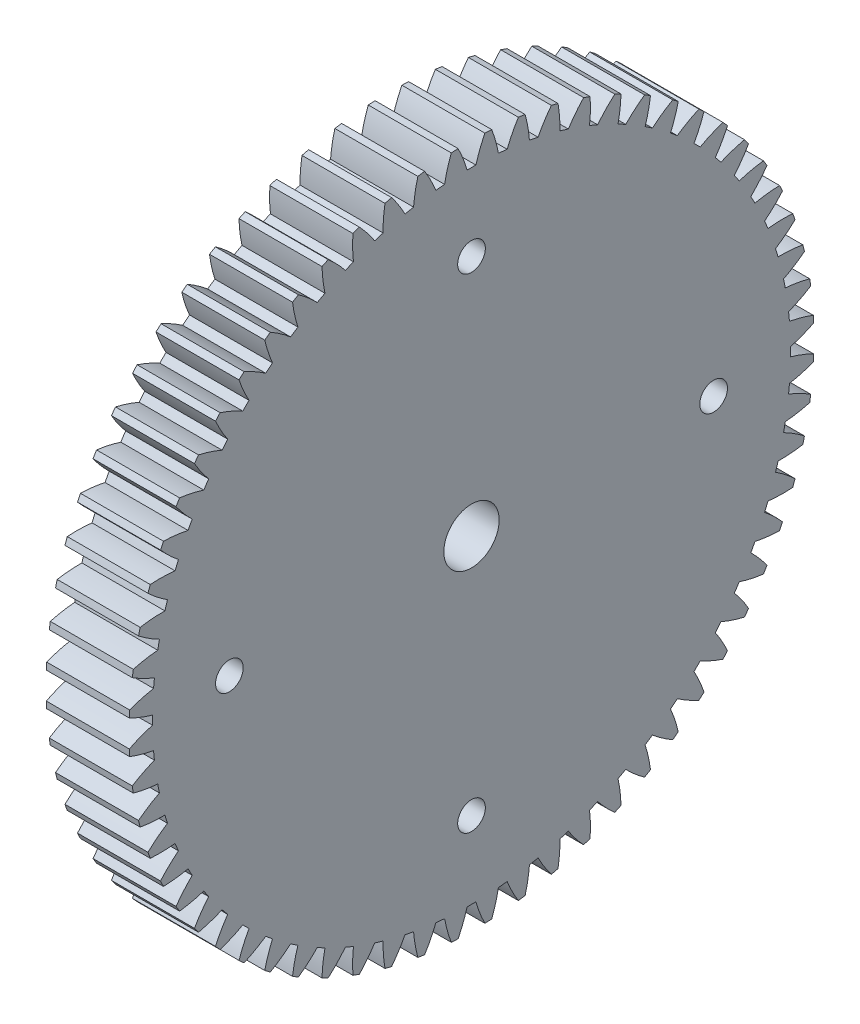
SolidWorks part; units mm, degrees
ref_plane "Plane1" through (0, 0, 0) normal (0, 0, 1) x (1, 0, 0)
ref_plane "Plane2" through (0, 0, 0) normal (0, 1, 0) x (1, 0, 0)
ref_plane "Plane3" through (0, 0, 0) normal (1, 0, 0) x (0, 0, -1)
sketch "HoldingSke" plane through (0, 0, 0) normal (0, 1, 0) x (1, 0, 0)
  line L0 (0, 0) -> (0.2922, -0.5992)
  line L1 (-15, 0) -> (100, 0) construction
  line L2 (0, 0) -> (-2.1039, 2.3779)
  line L3 (0, 0) -> (-11.863, 4.5341)
  line L4 (0, 0) -> (3.7858, 7.762)
  line L5 (0, 0) -> (-46.8476, -17.4728)
  line L6 (0, 0) -> (-9.9476, -6.7116)
  line L7 (-2.1039, 2.3779) -> (8.6586, 51.2059)
  line L8 (-76.2, 54.61) -> (-74.8, 54.61)
  line L9 (-71.009, 38.7566) -> (-53.1078, 45.2721)
  line L10 (-76.2, 71.12) -> (104.1128, 71.12)
  line L11 (0, 0) -> (-12, 0)
  line L12 (-76.2, 101.6) -> (-76.147, 101.6)
  line L13 (24.9733, 27.94) -> (52.9518, 28.4284)
  line L14 (24.9733, 27.94) -> (24.9743, 27.94)
  line L15 (24.9733, 27.94) -> (100.4006, 29.5858)
  line L16 (-63.627, -1.5) -> (-12.827, -1.5)
  circle A0 centre (0, 0) radius 4
  circle A1 centre (0, 0) radius 37.5
  circle A2 centre (0, 0) radius 37.5
  circle A3 centre (0, 0) radius 4
  dimension "MHD" = 75
  dimension "Hub_dia" = 75
  dimension "Bore" = 8
  dimension "MBD" = 8
  dimension "Num_teeth" = 64
  dimension "Pitch" = 0.6667
  dimension "Overall_len" = 50
  dimension "Show_teeth" = 64
  dimension "Thickness" = 12
  dimension "OAL" = 50.0001
  dimension "T_dim" = 1.4
  dimension "Ap" = 20
  dimension "H" = 19.05
  dimension "Pitch_radius" = 180.3128
  dimension "Width" = 12
  dimension "Backlash" = 0.053
  dimension "Addendum_fac" = 1
  dimension "Dedendum_fac" = 1.25
  dimension "Clearance_fac" = 0.25
  dimension "Dedendum_add" = 0.001
  dimension "Module" = 1.5
sketch "BasProSke" plane through (0, 0, 0) normal (0, 1, 0) x (1, 0, 0)
  line L0 (-10, 0) -> (60, 0) construction
  line L1 (0, 0) -> (0, 49.5)
  line L2 (0, 0) -> (12, 0)
  line L3 (12, 0) -> (12, 49.5)
  line L4 (12, 49.5) -> (0, 49.5)
  dimension "Thickness" = 12
  dimension "Diameter" = 99
revolve "Base-Revolve" add sketch "BasProSke" angle 360 about L0
sketch "TooCutSke" plane through (0, 0, 0) normal (1, 0, 0) x (0, 0, -1)
  line L1 (0, 0) -> (0, 107) construction
  line L2 (0, 0) -> (-1.2707, 47.9832) construction
  line L3 (0, 0) -> (-4.7093, 95.8599) construction
  line L4 (-1.2707, 47.9832) -> (-2.3546, 47.9299) construction
  arc A0 (0.6351, 46.1196) -> (-0.6351, 46.1196) centre (0, 0) ccw
  arc A1 (1.9477, 49.4871) -> (-1.9477, 49.4871) centre (0, 0) ccw
  circle A2 centre (0, 0) radius 48 construction
  circle A3 centre (0, 0) radius 45.1052 construction
  arc A4 (-0.6351, 46.1196) -> (-1.9477, 49.4871) centre (-19.101, 40.8612) ccw
  arc A5 (1.9477, 49.4871) -> (0.6351, 46.1196) centre (19.101, 40.8612) ccw
  dimension "Root_dia" = 92.248
  dimension "Overcut_dia" = 99.0508
  dimension "Pitch_dia" = 96
  dimension "Base_dia" = 90.2105
  dimension "Flank_rad" = 19.2
  dimension "Half_ang" = 2.813
  dimension "Half_CT" = 1.0852
extrude "ToothCut" cut sketch "TooCutSke" along normal through all
fillet "Breaks" [suppressed] radius 0.03
fillet "RootFillets" [suppressed] radius 0.376
pattern_circular "TeethCuts" count 64 every 5.625 about axis through (-10, 0, 0) along (1, 0, 0) of "ToothCut", "RootFillets", "Breaks"
sketch "HubNeaOneSke" plane through (0, 0, 0) normal (-1, 0, 0) x (0, 0, 1)
  circle A0 centre (0, 0) radius 37.5
  dimension "Diameter" = 75
extrude "HubNearOne" [suppressed] add sketch "HubNeaOneSke" along normal blind 38.0001
sketch "HubNeaBotSke" plane through (0, 0, 0) normal (-1, 0, 0) x (0, 0, 1)
  circle A0 centre (0, 0) radius 37.5
  dimension "Diameter" = 75
extrude "HubNearBoth" [suppressed] add sketch "HubNeaBotSke" along normal blind 19
ref_plane "FarPln" through (12, 0, 0) normal (1, 0, 0) x (0, 0, -1)
sketch "HubFarSke" plane through (12, 0, 0) normal (1, 0, 0) x (0, 0, -1)
  circle A0 centre (0, 0) radius 37.5
  dimension "Diameter" = 75
extrude "HubFar" [suppressed] add sketch "HubFarSke" along normal blind 19
sketch "BorSke" plane through (0, 0, 0) normal (1, 0, 0) x (0, 0, -1)
  circle A0 centre (0, 0) radius 4
  dimension "Diameter" = 8
extrude "Bore" cut sketch "BorSke" along normal mid plane 100.0001
sketch "KeySke" plane through (0, 0, 0) normal (1, 0, 0) x (0, 0, -1)
  line L0 (-1.5, 0) -> (-1.5, 5.4)
  line L1 (-1.5, 5.4) -> (1.5, 5.4)
  line L2 (1.5, 5.4) -> (1.5, 0)
  line L3 (0, 0) -> (0, 34) construction
  line L4 (-1.5, 0) -> (1.5, 0)
  dimension "Offset" = 5.4
  dimension "Width" = 3
extrude "Keyway" [suppressed] cut sketch "KeySke" along normal mid plane 100.0001
pattern_circular "Keyway2" [suppressed] count 2 every 90 about axis through (-10, 0, 0) along (1, 0, 0)
sketch "Sketch3" plane through (12, 0, 0) normal (1, 0, 0) x (0, 0, -1)
  line L0 (0, 0) -> (0, 35) construction
  line L1 (0, 43.7615) -> (0, 0) construction
  line L2 (0, 0) -> (70.0912, 0) construction
  line L3 (-35, 0) -> (0, 0) construction
  line L5 (0, -35) -> (0, 0) construction
  line L6 (35, 0) -> (0, 0) construction
  circle A0 centre (0, 35) radius 2
  circle A1 centre (35, 0) radius 2
  circle A2 centre (0, -35) radius 2
  circle A3 centre (-35, 0) radius 2
  point P6 (0, 0)
  point P15 (0, 40)
  dimension "D2" = 4
  dimension "D1" = 35
extrude "Cut-Extrude1" cut sketch "Sketch3" against normal through all
equation "' \"Module@HoldingSke\" = 6.35"
equation "' \"Num_teeth@HoldingSke\" = 12"
equation "' \"Ap@HoldingSke\" =  20"
equation "' \"Ap@HoldingSke\" = 20"
equation "' \"Width@HoldingSke\" = 0.5 * 25.4"
equation "' \"Hub_dia@HoldingSke\"= 1 * 25.4"
equation "' \"Hub_dia@HoldingSke\" = 1 * 25.4"
equation "' \"Overall_len@HoldingSke\" = 1.0 * 25.4"
equation "' \"Bore@HoldingSke\" = 0.75 * 25.4"
equation "' \"T_dim@HoldingSke\" = 0.1 * 25.4"
equation "' \"Width@KeySke\" = 0.25 * 25.4"
equation "' \"Show_teeth@HoldingSke\" = 13"
equation "' \"Backlash@HoldingSke\" = 0.009 * 25.4"
equation "' \"Addendum_fac@HoldingSke\" = 1.0"
equation "' \"Dedendum_fac@HoldingSke\" = 1.25"
equation "' \"Dedendum_add@HoldingSke\" = 0.00005 * 25.4"
equation "' \"Clearance_fac@HoldingSke\" = 0.25"
equation "\"Pitch@HoldingSke\" = 1 / \"Module@HoldingSke\""
equation "\"Overcut_dia@TooCutSke\" = (\"Num_teeth@HoldingSke\" + 2 * \"Addendum_fac@HoldingSke\") / \"Pitch@HoldingSke\" + 0.002 * 25.4"
equation "\"Pitch_dia@TooCutSke\" = \"Num_teeth@HoldingSke\" / \"Pitch@HoldingSke\""
equation "\"Base_dia@TooCutSke\" = \"Num_teeth@HoldingSke\" / \"Pitch@HoldingSke\" * cos((\"Ap@HoldingSke\"  * 3.14159265 / 180))"
equation "\"Root_dia@TooCutSke\" = (\"Num_teeth@HoldingSke\" + 2) / \"Pitch@HoldingSke\" - 2 * (\"Addendum_fac@HoldingSke\" + \"Dedendum_fac@HoldingSke\") / \"Pitch@HoldingSke\" - \"Dedendum_add@HoldingSke\" * 2"
equation "\"Half_ang@TooCutSke\" = 180 / \"Num_teeth@HoldingSke\""
equation "\"Half_CT@TooCutSke\" = \"Num_teeth@HoldingSke\" / \"Pitch@HoldingSke\" * sin((3.14159265 / 2 / \"Num_teeth@HoldingSke\")) / 2 - 7 * \"Backlash@HoldingSke\" / 4"
equation "\"Flank_rad@TooCutSke\" = \"Num_teeth@HoldingSke\" / \"Pitch@HoldingSke\" / 5"
equation "\"Radius@RootFillets\" = \"Clearance_fac@HoldingSke\" / \"Pitch@HoldingSke\" + \"Dedendum_add@HoldingSke\""
equation "\"Break_rad@Breaks\" = 0.02 / \"Pitch@HoldingSke\""
equation "\"Thickness@HoldingSke\" = \"Width@HoldingSke\""
equation "\"OAL@HoldingSke\" = \"Thickness@HoldingSke\""
equation "\"MHD@HoldingSke\" = (\"Num_teeth@HoldingSke\" + 2) / \"Pitch@HoldingSke\" - 2 * (\"Addendum_fac@HoldingSke\" + \"Dedendum_fac@HoldingSke\")  / \"Pitch@HoldingSke\" - \"Dedendum_add@HoldingSke\" * 2"
equation "\"MBD@HoldingSke\" = (\"Num_teeth@HoldingSke\" + 2) / \"Pitch@HoldingSke\" - 2 * (\"Addendum_fac@HoldingSke\" + \"Dedendum_fac@HoldingSke\")  / \"Pitch@HoldingSke\" - \"Dedendum_add@HoldingSke\" * 2 - 0.002 * 25.4"
equation "\"MHD@HoldingSke\" = ((sgn( \"MHD@HoldingSke\" - \"Hub_dia@HoldingSke\" )-1)*( \"MHD@HoldingSke\" - \"Hub_dia@HoldingSke\" ))/-2+ \"Hub_dia@HoldingSke\""
equation "\"MBD@HoldingSke\" = ((sgn( \"MBD@HoldingSke\" - \"Bore@HoldingSke\" )-1)*( \"MBD@HoldingSke\" - \"Bore@HoldingSke\" ))/-2+ \"Bore@HoldingSke\""
equation "\"OAL@HoldingSke\" = ((sgn( \"OAL@HoldingSke\" - \"Overall_len@HoldingSke\" )+1)*( \"OAL@HoldingSke\" - \"Overall_len@HoldingSke\" ))/2 + \"Overall_len@HoldingSke\" + 0.000002 * 25.4"
equation "\"Num_teeth@TeethCuts\" = int( \"Show_teeth@HoldingSke\" ) + 1"
equation "\"Num_teeth@TeethCuts\" = ((sgn( \"Num_teeth@TeethCuts\" - \"Num_teeth@HoldingSke\" )-1)*( \"Num_teeth@TeethCuts\" - \"Num_teeth@HoldingSke\" ))/-2+ \"Num_teeth@HoldingSke\""
equation "\"Num_teeth@TeethCuts\" = ((sgn( \"Num_teeth@TeethCuts\" - 2.0)+1)*( \"Num_teeth@TeethCuts\" - 2.0))/2 +2.0"
equation "\"Angle@TeethCuts\" = 360.0 / \"Num_teeth@HoldingSke\""
equation "\"Diameter@BasProSke\" = (\"Num_teeth@HoldingSke\" + 2 * \"Addendum_fac@HoldingSke\") / \"Pitch@HoldingSke\""
equation "\"Thickness@BasProSke\"  = \"Thickness@HoldingSke\""
equation "' \"Fillet_rad@BasProSke\" =  \"Thickness@HoldingSke\" * 0.05"
equation "' \"Fillet_rad@BasProSke\" = \"Thickness@HoldingSke\" * 0.05"
equation "\"MHD@HoldingSke\" = ((sgn( \"MHD@HoldingSke\" - \"Root_dia@TooCutSke\" )-1)*( \"MHD@HoldingSke\" - \"Root_dia@TooCutSke\" ))/-2+ \"Root_dia@TooCutSke\""
equation "\"Diameter@HubNeaOneSke\" = \"MHD@HoldingSke\""
equation "\"Length@HubNearOne\" = \"OAL@HoldingSke\" - \"Thickness@BasProSke\""
equation "\"Diameter@HubNeaBotSke\" = \"MHD@HoldingSke\""
equation "\"Length@HubNearBoth\" = ( \"OAL@HoldingSke\" - \"Thickness@BasProSke\" ) / 2.0"
equation "\"Thickness@FarPln\" = \"Thickness@BasProSke\""
equation "\"Diameter@HubFarSke\" = \"MHD@HoldingSke\""
equation "\"Length@HubFar\" = ( \"OAL@HoldingSke\" - \"Thickness@BasProSke\" ) / 2.0"
equation "\"Diameter@BorSke\" = \"MBD@HoldingSke\""
equation "\"D1@Bore\" = \"OAL@HoldingSke\" * 2.0"
equation "\"D1@Keyway\" = \"OAL@HoldingSke\" * 2.0"
equation "\"Offset@KeySke\" = \"T_dim@HoldingSke\" + \"MBD@HoldingSke\" / 2.0"
